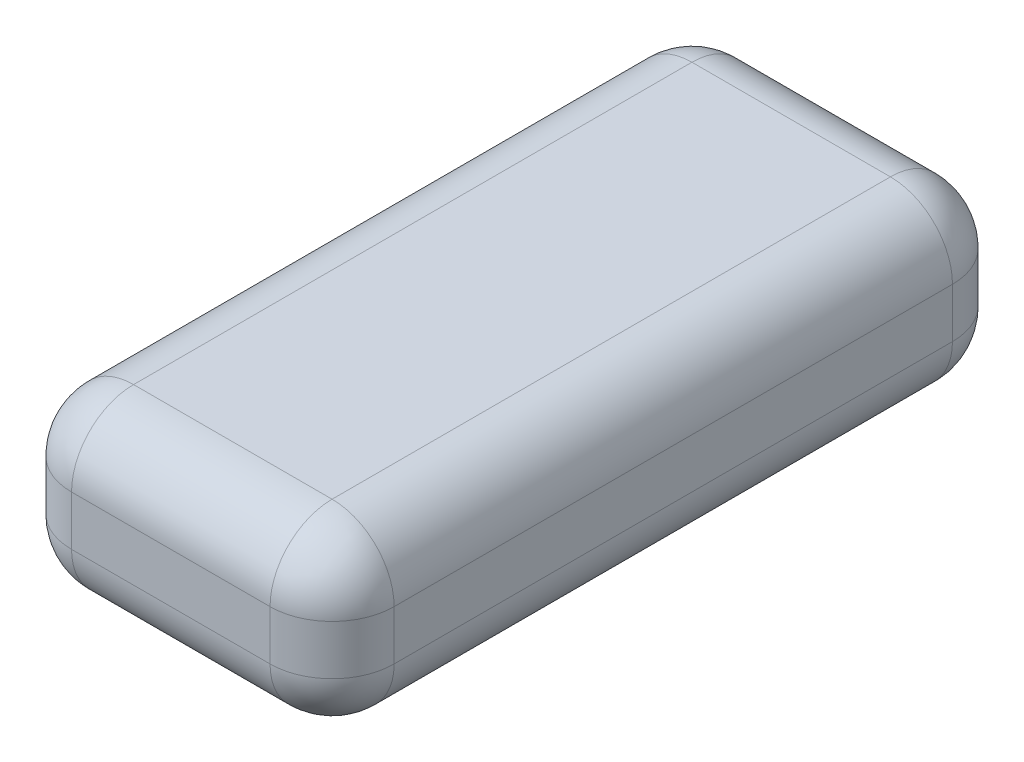
SolidWorks part; units mm, degrees
ref_plane "正面" through (0, 0, 0) normal (0, 0, 1) x (1, 0, 0)
ref_plane "平面" through (0, 0, 0) normal (0, 1, 0) x (1, 0, 0)
ref_plane "右側面" through (0, 0, 0) normal (1, 0, 0) x (0, 0, -1)
sketch "ｽｹｯﾁ1" plane through (0, 0, 0) normal (0, 0, 1) x (1, 0, 0)
  line L1 (26, -14) -> (-26, -14)
  line L2 (26, -14) -> (26, 14)
  line L3 (26, 14) -> (-26, 14)
  line L4 (-26, -14) -> (-26, 14)
  line L5 (26, -14) -> (-26, 14) construction
  line L6 (26, 14) -> (-26, -14) construction
  point P0 (0, 0)
  dimension "D1" = 52
  dimension "D2" = 28
extrude "ﾎﾞｽ - 押し出し1" add sketch "ｽｹｯﾁ1" along normal blind 110
fillet "ﾌｨﾚｯﾄ1" radius 10 12 edges at (0, 14, 0) (26, 0, 0) (26, -14, 55) (0, -14, 110) (-26, 0, 110) (26, 0, 110) (26, 14, 55) (0, 14, 110) (-26, 14, 55) (-26, -14, 55) (-26, 0, 0) (0, -14, 0)
